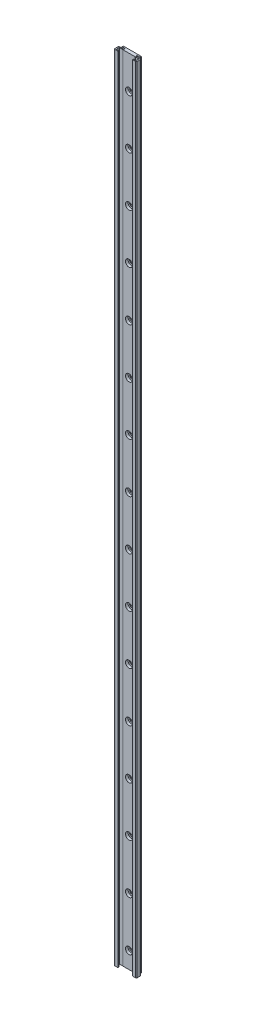
SolidWorks part; units mm, degrees
ref_plane "Plan de face" through (0, 0, 0) normal (0, 0, 1) x (1, 0, 0)
ref_plane "Plan de dessus" through (0, 0, 0) normal (0, 1, 0) x (1, 0, 0)
ref_plane "Plan de droite" through (0, 0, 0) normal (1, 0, 0) x (0, 0, -1)
ref_plane "Plan1" through (0, 0, 0) normal (0, -1, 0) x (1, 0, 0)
sketch "Esquisse1" plane through (0, 0, 0) normal (0, -1, 0) x (1, 0, 0)
  line L0 (13.5, 3) -> (13.5, 8.7)
  line L1 (13.5, 8.7) -> (-13.5, 8.7)
  line L2 (-13.5, 8.7) -> (-13.5, 3)
  line L3 (-13.5, 3) -> (-7.8, 3)
  line L4 (-7.8, 1.5) -> (-11, 1.5)
  line L5 (-11, 1.5) -> (-11, 0)
  line L6 (-11, 0) -> (11, 0)
  line L7 (11, 0) -> (11, 1.5)
  line L8 (11, 1.5) -> (7.8, 1.5)
  line L9 (7.8, 3) -> (13.5, 3)
  arc A0 (-7.8, 3) -> (-7.8, 1.5) centre (-7.8, 2.25) cw
  arc A1 (7.8, 1.5) -> (7.8, 3) centre (7.8, 2.25) cw
extrude "Boss.-Extru.1" add sketch "Esquisse1" against normal blind 960
sketch "Esquisse2" plane through (0, 960, 0) normal (0, 1, 0) x (-1, 0, 0)
  line L0 (8.75, 8.7) -> (-8.75, 8.7)
  line L1 (-8.75, 8.7) -> (-8.75, 7.6)
  line L2 (-8.75, 7.6) -> (-12, 7.6)
  line L3 (-12, 7.6) -> (-12, 4.1)
  line L4 (-12, 4.1) -> (12, 4.1)
  line L5 (12, 4.1) -> (12, 7.6)
  line L6 (12, 7.6) -> (8.75, 7.6)
  line L7 (8.75, 7.6) -> (8.75, 8.7)
extrude "Enlèv. mat.-Extru.1" cut sketch "Esquisse2" against normal through all
hole_wizard "Diamètre du perçage Ø0.4 (0.4)1" positions "Esquisse4" profile "Esquisse3" hole size "Ø0.4" standard "Ansi Metric"
sketch "Esquisse4" plane through (0, 0, 0) normal (0, -1, 0) x (-1, 0, 0)
  point P0 (7.75, -4.1)
  point P1 (-7.75, -4.1)
sketch "Esquisse3" plane through (-7.75, 0, 4.1) normal (1, 0, 0) x (0, 0, -1)
  line L0 (0, 0) -> (0, 960)
  line L1 (0, 960) -> (0.2, 960)
  line L2 (0.2, 960) -> (0.2, 0)
  line L5 (0.2, 0) -> (0, 0)
  line L11 (0, -6.35) -> (0, 107.95) construction
  dimension "Diamètre du perçage jusqu'au prochain" = 0.4
  dimension "Profondeur du perçage jusqu'au prochain" = 960
hole_wizard "Chambrage pour vis à tête hexagonale M41" positions "Esquisse6" profile "Esquisse5" counterbore size "M4" standard "Ansi Metric"
sketch "Esquisse6" plane through (0, 0, 4.1) normal (0, 0, 1) x (1, 0, 0)
  point P0 (0, 20)
  point P1 (0, 80)
sketch "Esquisse5" plane through (0, 20, 4.1) normal (1, 0, 0) x (0, -1, 0)
  line L0 (0, 0) -> (0, 4.1)
  line L1 (0, 4.1) -> (2.25, 4.1)
  line L3 (2.25, 4.1) -> (2.25, 3.1)
  line L4 (2.25, 3.1) -> (4.25, 3.1)
  line L5 (4.25, 3.1) -> (4.25, 0)
  line L7 (4.25, 0) -> (0, 0)
  line L11 (0, -6.35) -> (0, 107.95) construction
  dimension "Diamètre du perçage jusqu'au prochain" = 4.5
  dimension "Profondeur du perçage jusqu'au prochain" = 4.1
  dimension "Diamètre du chambrage" = 8.5
  dimension "Profondeur du chambrage" = 3.1
fillet "Congé1" radius 0.2 2 edges at (11, 480, 1.5) (-11, 480, 1.5)
fillet "Congé2" radius 0.5 4 edges at (12, 480, 7.6) (-12, 480, 7.6) (-12, 480, 4.1) (12, 480, 4.1)
fillet "Congé3" radius 1 4 edges at (-13.5, 480, 3) (13.5, 480, 3) (-13.5, 480, 8.7) (13.5, 480, 8.7)
pattern_linear "Répétition linéaire1" count 16 spacing 60 along (0, 1, 0) of "Chambrage pour vis à tête hexagonale M41"
